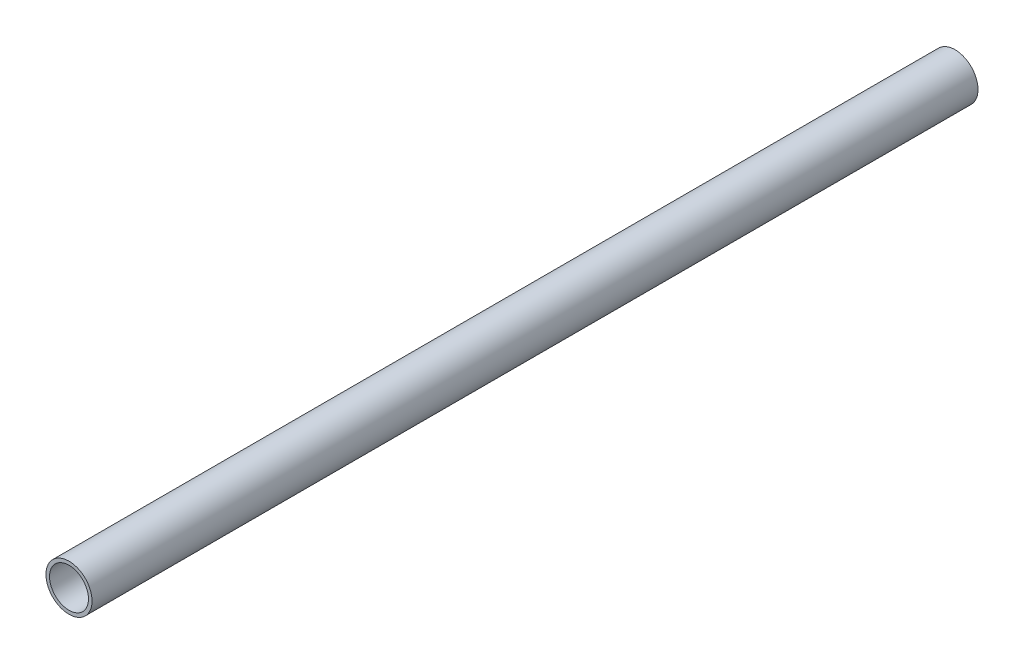
SolidWorks part; units mm, degrees
material "Alliage 1060"
ref_plane "Plan de face" through (0, 0, 0) normal (0, 0, 1) x (1, 0, 0)
ref_plane "Plan de dessus" through (0, 0, 0) normal (0, 1, 0) x (1, 0, 0)
ref_plane "Plan de droite" through (0, 0, 0) normal (1, 0, 0) x (0, 0, -1)
sketch "Esquisse1" plane through (0, 0, 0) normal (0, 0, 1) x (1, 0, 0)
  circle A0 centre (0, 0) radius 13
  circle A1 centre (0, 0) radius 11
  dimension "D1" = 26
  dimension "D2" = 2
extrude "Boss.-Extru.1" add sketch "Esquisse1" along normal blind 500
